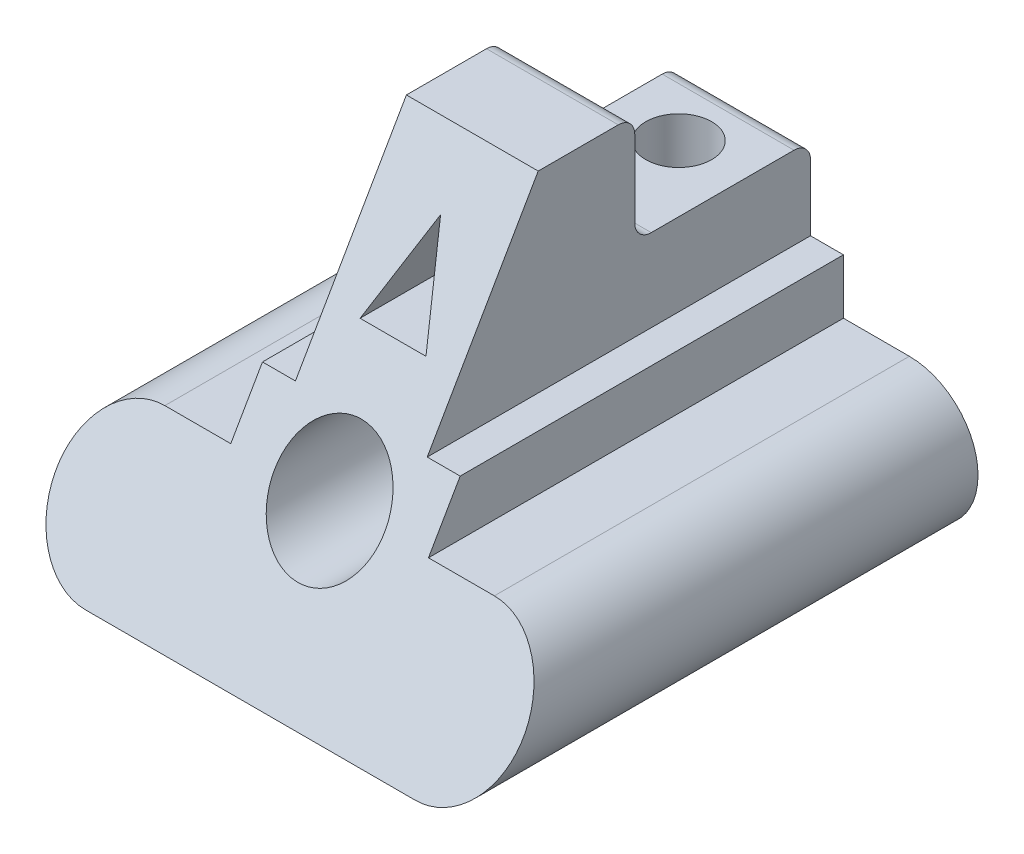
SolidWorks part; units mm, degrees
ref_plane "Front Plane" through (0, 0, 0) normal (0, 0, 1) x (1, 0, 0)
ref_plane "Top Plane" through (0, 0, 0) normal (0, 1, 0) x (1, 0, 0)
ref_plane "Right Plane" through (0, 0, 0) normal (1, 0, 0) x (0, 0, -1)
sketch "Sketch1" plane through (0, 0, 0) normal (0, 0, 1) x (1, 0, 0)
  line L0 (-30, 0) -> (30, 0) construction
  line L1 (0, 0) -> (0, 25.3192) construction
  line L2 (-30, -12.5) -> (30, -12.5)
  line L3 (-30, 12.5) -> (-18, 12.5)
  line L4 (-18, 12.5) -> (-18, 22.5)
  line L5 (-18, 22.5) -> (-12, 22.5)
  line L6 (-12, 22.5) -> (-12, 57.5)
  line L7 (-12, 57.5) -> (12, 57.5)
  line L8 (30, 12.5) -> (18, 12.5)
  line L9 (18, 12.5) -> (18, 22.5)
  line L10 (18, 22.5) -> (12, 22.5)
  line L11 (12, 22.5) -> (12, 57.5)
  arc A0 (-30, 12.5) -> (-30, -12.5) centre (-30, 0) ccw
  arc A1 (30, 12.5) -> (30, -12.5) centre (30, 0) cw
  point P3 (0, 0)
  point P11 (0, 0)
  point P20 (0, 57.5)
  dimension "D1" = 12.5
  dimension "D2" = 60
  dimension "D3" = 12
  dimension "D4" = 10
  dimension "D5" = 6
  dimension "D6" = 35
extrude "Boss-Extrude1" add sketch "Sketch1" along normal mid plane 90
sketch "Sketch2" plane through (0, 0, 0) normal (1, 0, 0) x (0, 0, -1)
  line L0 (-4.5855, 57.5) -> (-45, -12.5)
  line L1 (-45, 57.5) -> (45, 57.5) construction
  line L2 (-45, 22.5) -> (-45, 57.5) construction
  line L3 (-45, -12.5) -> (-45, 57.5)
  line L4 (-45, 57.5) -> (-4.5855, 57.5)
  dimension "D1" = 30
extrude "Cut-Extrude1" cut sketch "Sketch2" against normal through all both and the other way through all
sketch "Sketch3" plane through (0, 0, 0) normal (0, 0, 1) x (1, 0, 0)
  line L0 (-30, -12.5) -> (30, -12.5) construction
  line L1 (0, 47.5) -> (-6, 32.5)
  line L2 (-6, 32.5) -> (6, 32.5)
  line L3 (6, 32.5) -> (0, 47.5)
  circle A0 centre (0, 12.5) radius 10
  point P4 (0, 0)
  point P9 (0, 32.5)
  dimension "D1" = 20
  dimension "D2" = 25
  dimension "D3" = 12
  dimension "D4" = 45
  dimension "D5" = 15
extrude "Cut-Extrude2" cut sketch "Sketch3" along normal through all
sketch "Sketch5" plane through (-12, 0, 0) normal (-1, 0, 0) x (0, 0, 1)
  line L0 (24.7927, 22.5) -> (-45, 22.5) construction
  line L1 (-45, 57.5) -> (-13, 57.5)
  line L2 (-45, 57.5) -> (-45, 37.5)
  line L3 (-45, 37.5) -> (-13, 37.5)
  line L4 (-13, 57.5) -> (-13, 37.5)
  dimension "D1" = 32
  dimension "D2" = 15
extrude "Cut-Extrude3" cut sketch "Sketch5" against normal through all both and the other way through all
sketch "Sketch4" plane through (0, 57.5, 0) normal (0, 1, 0) x (1, 0, 0)
  line L1 (-12, 45) -> (12, 45) construction
  circle A0 centre (0, 33) radius 6
  point P2 (0, 0)
  dimension "D1" = 12
  dimension "D2" = 12
extrude "Cut-Extrude4" cut sketch "Sketch4" against normal through all both and the other way through all
fillet "Fillet1" radius 3 3 edges at (0, 57.5, -13) (0, 37.5, -13) (0, 37.5, -45)
